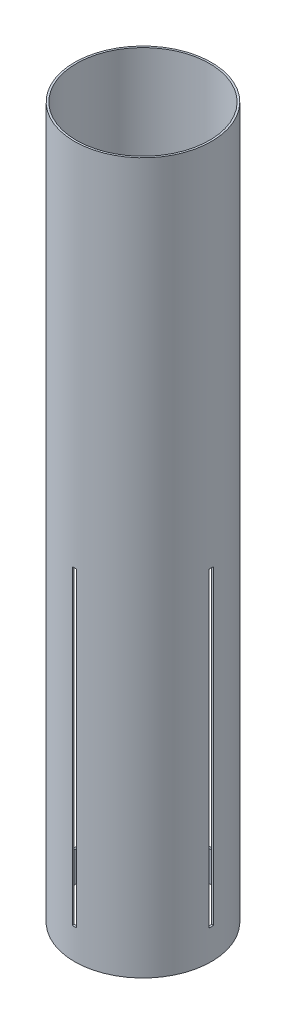
SolidWorks part; units mm, degrees
material "E-Glass Fiber"
ref_plane "Front Plane" through (0, 0, 0) normal (0, 0, 1) x (1, 0, 0)
ref_plane "Top Plane" through (0, 0, 0) normal (0, 1, 0) x (1, 0, 0)
ref_plane "Right Plane" through (0, 0, 0) normal (1, 0, 0) x (0, 0, -1)
sketch "Sustainer Tube Profile" plane through (0, 0, 0) normal (0, 1, 0) x (1, 0, 0)
  circle A0 centre (0, 0) radius 76.2
  circle A1 centre (0, 0) radius 78.359
  dimension "D1" = 152.4
  dimension "D2" = 156.718
extrude "Sustainer Tube Body" add sketch "Sustainer Tube Profile" along normal blind 812.8
ref_plane "Plane1" through (0, 0, 78.359) normal (0, 0, 1) x (1, 0, 0)
sketch "Fin Slot Profile" plane through (0, 0, 78.359) normal (0, 0, 1) x (1, 0, 0)
  line L0 (0, 0) -> (0, 812.8) construction
  line L5 (76.2, 812.8) -> (-76.2, 812.8) construction
  line L6 (-78.359, 0) -> (78.359, 0) construction
  line L7 (2.54, 34.671) -> (-2.54, 34.671)
  line L8 (0, 34.671) -> (0, 390.271)
  line L9 (2.54, 390.271) -> (-2.54, 390.271)
  line L10 (-2.54, 34.671) -> (-2.54, 390.271)
  line L11 (2.54, 34.671) -> (2.54, 390.271)
  dimension "D1" = 355.6
  dimension "D2" = 34.671
  dimension "D3" = 2.54
extrude "Fin Slot Cut" cut sketch "Fin Slot Profile" against normal up to surface (2.2013 mm away) contours L7 L11 L9 L8 | L10 L7 L8 L9
pattern_circular "Fin Slot Pattern" count 4 over 360 about axis through (0, 0, 0) along (0, 1, 0) of "Fin Slot Cut"
equation "\"Length\"= 32"
equation "\"Outer Diameter\"= 6.17"
equation "\"Inner Diameter\"= 6"
equation "\"Wall Thickness\"= 0.085"
equation "\"D1@Sustainer Tube Profile\" = \"Inner Diameter\""
equation "\"D2@Sustainer Tube Profile\" = \"Outer Diameter\""
equation "\"D1@Sustainer Tube Body\" = \"Length\""
equation "\"Root Chord\"= 14"
equation "\"Fin Offset\" = 1.365"
equation "\"D1@Fin Slot Profile\"=\"Root Chord\" "
equation "\"D2@Fin Slot Profile\" = \"Fin Offset\""
equation "\"Fin Thickness\"= 0.1"
equation "\"D3@Fin Slot Profile\"=\"Fin Thickness\""
